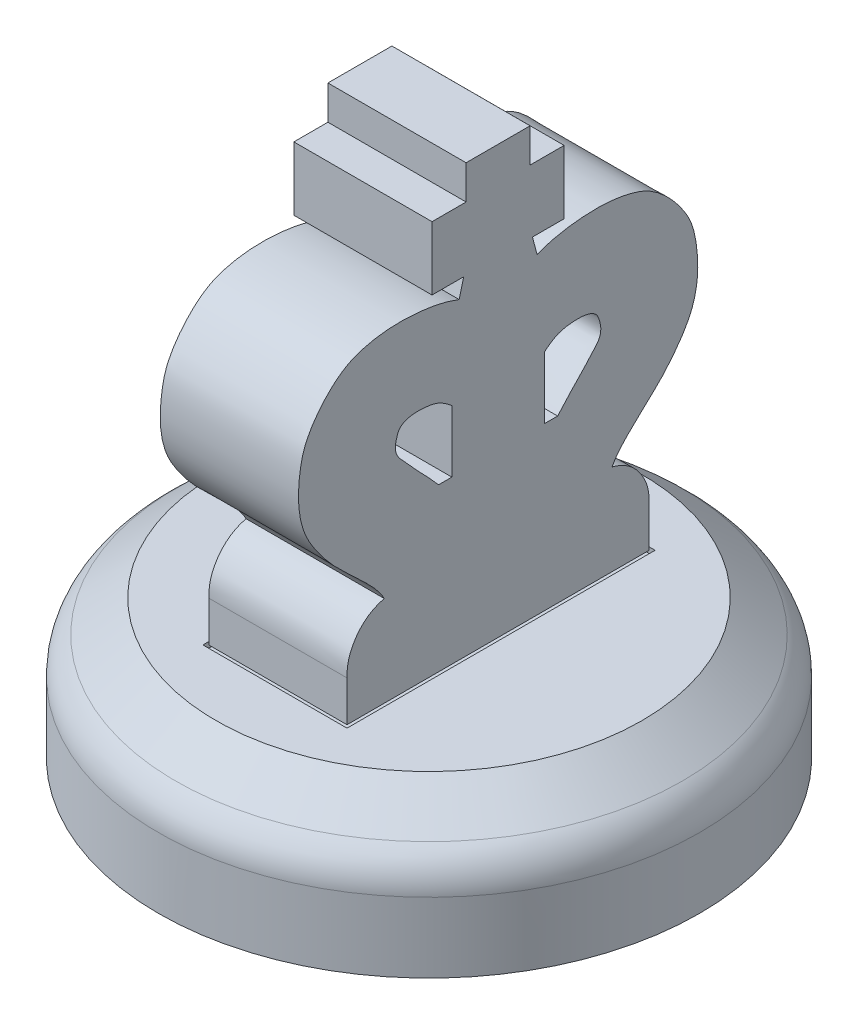
SolidWorks part; units mm, degrees
ref_plane "Front" through (0, 0, 0) normal (0, 0, 1) x (1, 0, 0)
ref_plane "Top" through (0, 0, 0) normal (0, 1, 0) x (1, 0, 0)
ref_plane "Right" through (0, 0, 0) normal (1, 0, 0) x (0, 0, -1)
sketch "Sketch1" plane through (0, 0, 0) normal (0, 1, 0) x (1, 0, 0)
  circle A0 centre (0, 0) radius 18.6531
  dimension "D1" = 37.3062
extrude "Boss-Extrude1" add sketch "Sketch1" along normal blind 6.35
sketch "Sketch2" plane through (0, 0, 0) normal (0, 0, 1) x (1, 0, 0)
  line L0 (-18.6531, 6.35) -> (-14.6844, 9.525)
  line L1 (-14.6844, 9.525) -> (0, 9.525)
  line L2 (0, 9.525) -> (0, 6.35)
  line L3 (18.6531, 6.35) -> (-18.6531, 6.35) construction
  line L4 (0, 6.35) -> (-18.6531, 6.35)
  line L5 (-18.6531, 0) -> (18.6531, 0) construction
  dimension "D1" = 3.9688
  dimension "D2" = 9.525
revolve "Revolve1" add sketch "Sketch2" angle 360 about L2
fillet "Fillet1" radius 3.175 1 edges at (0, 6.35, 18.6531)
sketch "Sketch3" plane through (0, 0, 0) normal (0, -1, 0) x (1, 0, 0)
  line L1 (-6.4516, -9.6266) -> (6.4516, -9.6266)
  line L2 (-6.4516, -9.6266) -> (-6.4516, 9.6266)
  line L3 (-6.4516, 9.6266) -> (6.4516, 9.6266)
  line L4 (6.4516, -9.6266) -> (6.4516, 9.6266)
  line L5 (-6.4516, -9.6266) -> (6.4516, 9.6266) construction
  line L6 (-6.4516, 9.6266) -> (6.4516, -9.6266) construction
  point P0 (0, 0)
  dimension "D1" = 19.2532
  dimension "D2" = 12.9032
extrude "Cut-Extrude1" cut sketch "Sketch3" against normal mid plane 4.7625
hole_wizard "#6 (0.204) Diameter Hole1" positions "Sketch4" profile "Sketch5" hole size "#6" standard "ANSI Inch" end condition through all
sketch "Sketch4" plane through (0, 2.3813, 0) normal (0, -1, 0) x (-1, 0, 0)
  point P0 (0, 0)
sketch "Sketch5" plane through (0, 2.3813, 0) normal (1, 0, 0) x (0, 0, -1)
  line L0 (0, 0) -> (0, 7.1438)
  line L1 (0, 7.1438) -> (2.5908, 7.1438)
  line L2 (2.5908, 7.1438) -> (2.5908, 0)
  line L5 (2.5908, 0) -> (0, 0)
  line L11 (0, -6.35) -> (0, 107.95) construction
  dimension "Thru Hole Dia." = 5.1816
  dimension "Thru Hole Depth" = 7.1438
sketch "Sketch6" plane through (0, 0, 0) normal (1, 0, 0) x (0, 0, -1)
  line L0 (24.9405, 134.35) -> (195.6072, 134.35) construction
  line L1 (-10.414, 9.525) -> (10.414, 9.525)
  line L2 (14.6844, 9.525) -> (-14.6844, 9.525) construction
  line L3 (-10.414, 9.525) -> (-10.414, 12.319)
  line L4 (10.414, 9.525) -> (10.414, 12.319)
  line L5 (-2.6874, 31.0438) -> (-2.3677, 32.2449)
  line L6 (-2.3677, 32.2449) -> (-4.5525, 32.2449)
  line L7 (-4.5525, 32.2449) -> (-4.5525, 36.6239)
  line L8 (-4.5525, 36.6239) -> (-2.2062, 36.6239)
  line L9 (-2.2062, 36.6239) -> (-2.2062, 38.9674)
  line L10 (-3.1863, 20.6933) -> (-3.1863, 24.9649)
  line L11 (-3.1863, 20.6933) -> (-4.1048, 20.6933)
  line L12 (0, 50) -> (0, -50) construction
  line L13 (3.1863, 20.6933) -> (4.1048, 20.6933)
  line L14 (3.1863, 20.6933) -> (3.1863, 24.9649)
  line L15 (2.6874, 31.0438) -> (2.3677, 32.2449)
  line L16 (2.3677, 32.2449) -> (4.5525, 32.2449)
  line L17 (4.5525, 32.2449) -> (4.5525, 36.6239)
  line L18 (4.5525, 36.6239) -> (2.2062, 36.6239)
  line L19 (2.2062, 36.6239) -> (2.2062, 38.9674)
  line L20 (-2.2062, 38.9674) -> (2.2062, 38.9674)
  spline S0 degree 3 poles (-10.414, 12.319) (-10.414, 12.6253) (-10.3717, 13.407) (-9.8858, 14.4028) (-9.0286, 15.3233) (-8.3232, 15.6673) (-7.8467, 15.7758) knots 0 0 0 0 0.191944 0.510716 0.683896 1 1 1 1
  spline S1 degree 3 poles (-7.8467, 15.7758) (-8.205, 16.4445) (-9.0302, 17.2701) (-10.3673, 18.5314) (-11.5064, 19.6006) (-12.5546, 20.9529) (-13.3567, 22.2579) (-13.8141, 24.0439) (-13.7599, 25.8451) (-13.4345, 27.4684) (-12.8235, 28.6079) (-12.1329, 29.5283) (-11.2782, 30.3981) (-10.2948, 31.096) (-9.2513, 31.45) (-7.6159, 31.7831) (-5.3967, 31.7585) (-3.5356, 31.3839) (-2.6874, 31.0438) knots 0 0 0 0 0.085094 0.132048 0.209466 0.262245 0.326558 0.382121 0.469327 0.529647 0.568485 0.615345 0.66022 0.706911 0.750976 0.784442 0.896709 1 1 1 1
  spline S2 degree 3 poles (-3.1863, 24.9649) (-3.4961, 25.2312) (-4.0986, 25.6607) (-5.1427, 25.8058) (-5.9566, 25.816) (-6.5612, 25.616) (-6.872, 25.3162) (-6.994, 24.9428) (-7.096, 24.5316) (-7.0692, 24.1116) (-6.8753, 23.6936) (-6.5503, 23.3318) (-6.119, 22.8772) (-5.694, 22.384) (-4.9677, 21.6696) (-4.4592, 21.1041) (-4.1048, 20.6933) knots 0 0 0 0 0.127028 0.218334 0.319362 0.375606 0.408657 0.447792 0.493913 0.53894 0.573598 0.633524 0.687102 0.766505 0.833287 1 1 1 1
  spline S3 degree 3 poles (3.1863, 24.9649) (3.4961, 25.2312) (4.0986, 25.6607) (5.1427, 25.8058) (5.9566, 25.816) (6.5612, 25.616) (6.872, 25.3162) (6.994, 24.9428) (7.096, 24.5316) (7.0692, 24.1116) (6.8753, 23.6936) (6.5503, 23.3318) (6.119, 22.8772) (5.694, 22.384) (4.9677, 21.6696) (4.4592, 21.1041) (4.1048, 20.6933) knots 0 0 0 0 0.127028 0.218334 0.319362 0.375606 0.408657 0.447792 0.493913 0.53894 0.573598 0.633524 0.687102 0.766505 0.833287 1 1 1 1
  spline S4 degree 3 poles (10.414, 12.319) (10.414, 12.6253) (10.3717, 13.407) (9.8858, 14.4028) (9.0286, 15.3233) (8.3232, 15.6673) (7.8467, 15.7758) knots 0 0 0 0 0.191944 0.510716 0.683896 1 1 1 1
  spline S5 degree 3 poles (7.8467, 15.7758) (8.205, 16.4445) (9.0302, 17.2701) (10.3673, 18.5314) (11.5064, 19.6006) (12.5546, 20.9529) (13.3567, 22.2579) (13.8141, 24.0439) (13.7599, 25.8451) (13.4345, 27.4684) (12.8235, 28.6079) (12.1329, 29.5283) (11.2782, 30.3981) (10.2948, 31.096) (9.2513, 31.45) (7.6159, 31.7831) (5.3967, 31.7585) (3.5356, 31.3839) (2.6874, 31.0438) knots 0 0 0 0 0.085094 0.132048 0.209466 0.262245 0.326558 0.382121 0.469327 0.529647 0.568485 0.615345 0.66022 0.706911 0.750976 0.784442 0.896709 1 1 1 1
  point P6 (0, 9.525)
  dimension "D1" = 2.794
  dimension "D2" = 20.828
extrude "Boss-Extrude2" add sketch "Sketch6" along normal mid plane 9.525 separate body
sketch "Sketch7" plane through (0, 9.525, 0) normal (0, 1, 0) x (1, 0, 0)
  line L14 (-4.9657, -10.6172) -> (4.9657, -10.6172)
  line L15 (-4.9657, 10.6172) -> (-4.9657, -10.6172)
  line L16 (4.9657, 10.6172) -> (-4.9657, 10.6172)
  line L17 (4.9657, -10.6172) -> (4.9657, 10.6172)
  line L18 (-4.9657, -10.6172) -> (4.9657, -10.6172)
  line L19 (-4.9657, 10.6172) -> (-4.9657, -10.6172)
  line L20 (4.9657, 10.6172) -> (-4.9657, 10.6172)
  line L21 (4.9657, -10.6172) -> (4.9657, 10.6172)
  dimension "D1" = 0.2032
extrude "Cut-Extrude2" cut sketch "Sketch7" against normal blind 0.3969
